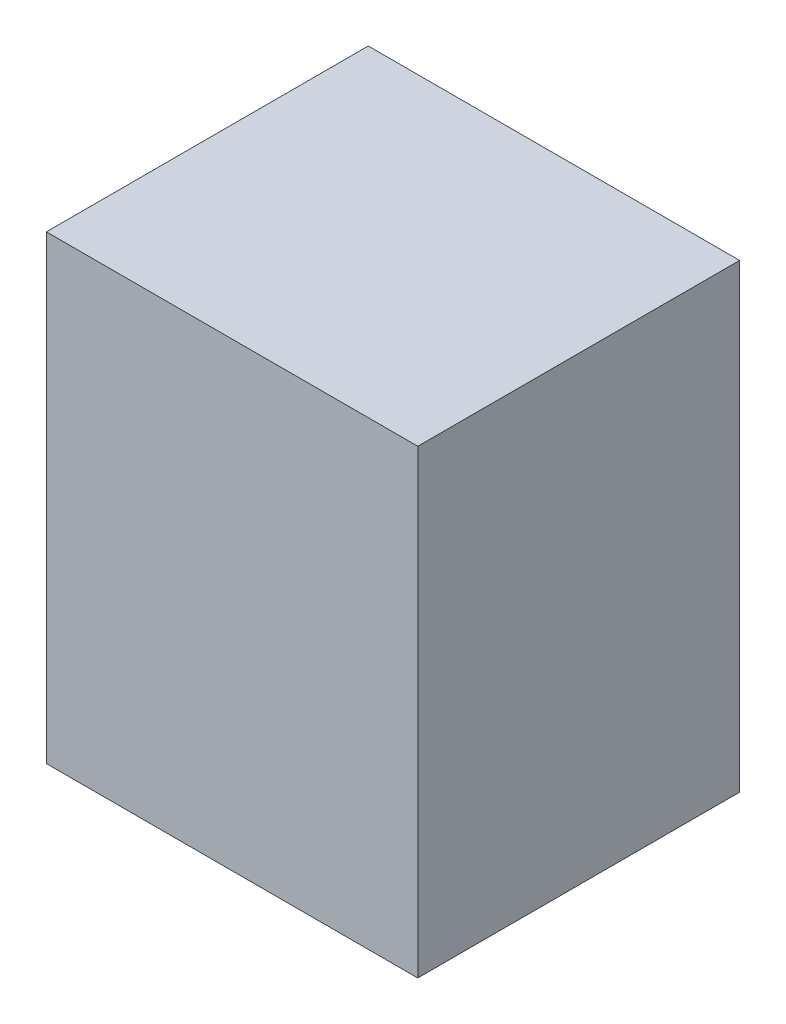
SolidWorks part; units mm, degrees
ref_plane "Ebene vorne" through (0, 0, 0) normal (0, 0, 1) x (1, 0, 0)
ref_plane "Ebene oben" through (0, 0, 0) normal (0, 1, 0) x (1, 0, 0)
ref_plane "Ebene rechts" through (0, 0, 0) normal (1, 0, 0) x (0, 0, -1)
sketch "Skizze1" plane through (0, 0, 0) normal (0, 1, 0) x (1, 0, 0)
  line L1 (-37.5, -32.5) -> (37.5, -32.5)
  line L2 (-37.5, -32.5) -> (-37.5, 32.5)
  line L3 (-37.5, 32.5) -> (37.5, 32.5)
  line L4 (37.5, -32.5) -> (37.5, 32.5)
  line L5 (-37.5, -32.5) -> (37.5, 32.5) construction
  line L6 (-37.5, 32.5) -> (37.5, -32.5) construction
  point P0 (0, 0)
  dimension "D1" = 75
  dimension "D2" = 65
extrude "Aufsatz-Linear austragen1" add sketch "Skizze1" along normal blind 93
